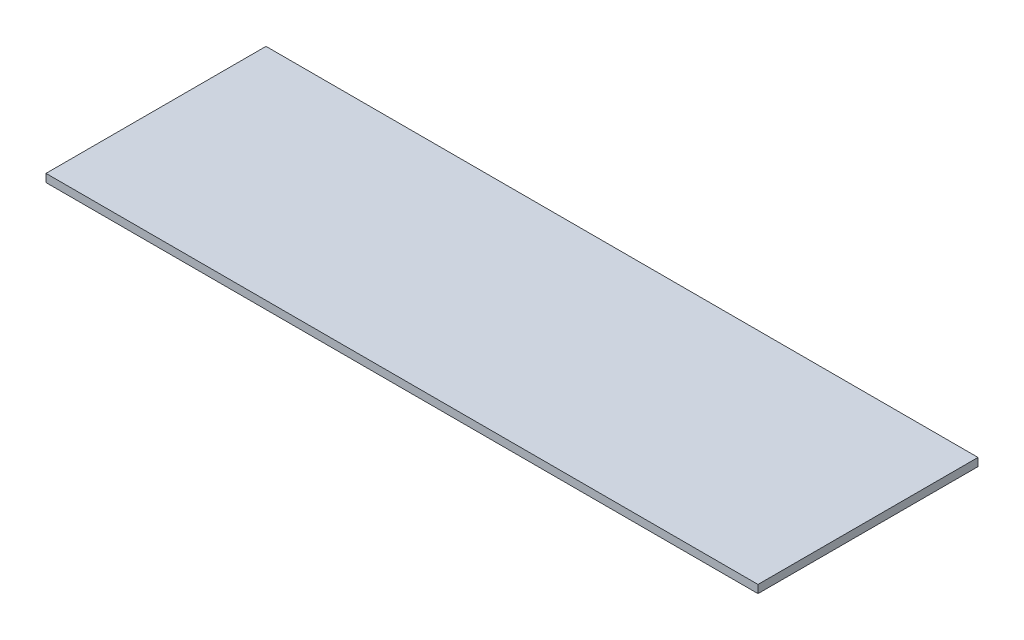
SolidWorks part; units mm, degrees
material "1060-H14"
ref_plane "Front Plane" through (0, 0, 0) normal (0, 0, 1) x (1, 0, 0)
ref_plane "Top Plane" through (0, 0, 0) normal (0, 1, 0) x (1, 0, 0)
ref_plane "Right Plane" through (0, 0, 0) normal (1, 0, 0) x (0, 0, -1)
sketch "Sketch1" plane through (0, 0, 0) normal (0, 1, 0) x (1, 0, 0)
  line L1 (-89, -27.5) -> (89, -27.5)
  line L2 (-89, -27.5) -> (-89, 27.5)
  line L3 (-89, 27.5) -> (89, 27.5)
  line L4 (89, -27.5) -> (89, 27.5)
  line L5 (-89, -27.5) -> (89, 27.5) construction
  line L6 (-89, 27.5) -> (89, -27.5) construction
  point P0 (0, 0)
  dimension "D1" = 55
  dimension "D2" = 178
extrude "Boss-Extrude1" add sketch "Sketch1" along normal blind 2
